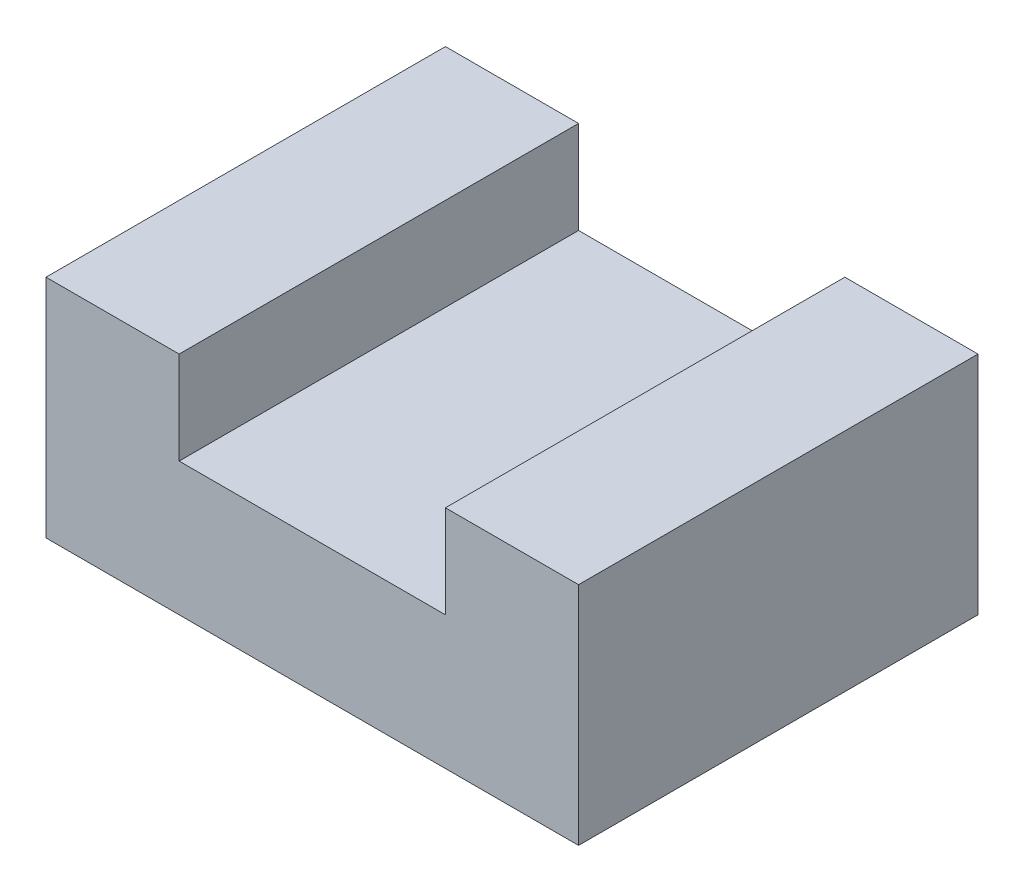
SolidWorks part; units mm, degrees
ref_plane "Front Plane" through (0, 0, 0) normal (0, 0, 1) x (1, 0, 0)
ref_plane "Top Plane" through (0, 0, 0) normal (0, 1, 0) x (1, 0, 0)
ref_plane "Right Plane" through (0, 0, 0) normal (1, 0, 0) x (0, 0, -1)
sketch "Sketch1" plane through (0, 0, 0) normal (0, 1, 0) x (1, 0, 0)
  line L1 (0, 15) -> (20, 15)
  line L2 (0, 15) -> (0, 0)
  line L3 (0, 0) -> (20, 0)
  line L4 (20, 15) -> (20, 0)
  dimension "D1" = 20
  dimension "D2" = 15
extrude "Boss-Extrude1" add sketch "Sketch1" along normal blind 5
sketch "Sketch3" plane through (0, 0, 0) normal (0, 0, 1) x (1, 0, 0)
  line L1 (0, 5) -> (5, 5)
  line L2 (0, 5) -> (0, 8.4808)
  line L3 (0, 8.4808) -> (5, 8.4808)
  line L4 (5, 5) -> (5, 8.4808)
  line L13 (20, 5) -> (15, 5)
  line L14 (20, 5) -> (20, 8.4808)
  line L15 (20, 8.4808) -> (15, 8.4808)
  line L16 (15, 5) -> (15, 8.4808)
  dimension "D1" = 5
  dimension "D2" = 3.4808
extrude "Boss-Extrude2" add sketch "Sketch3" against normal blind 15
